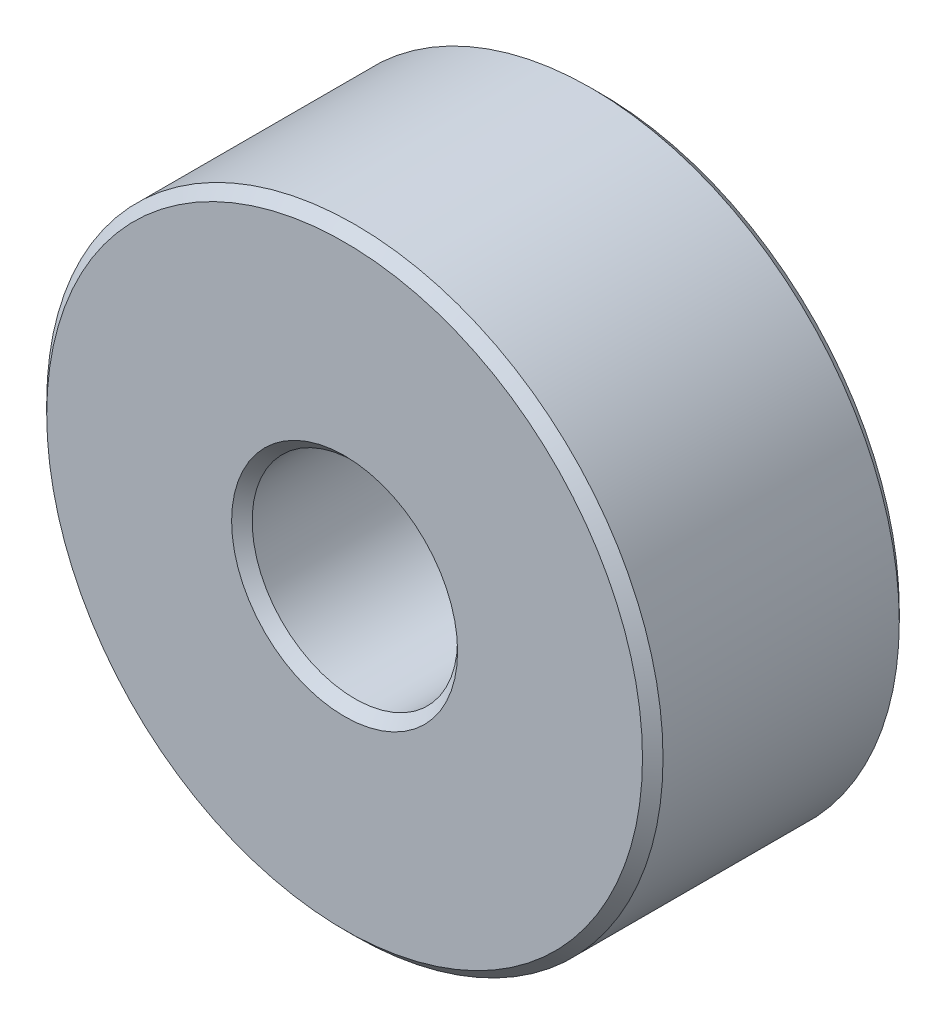
SolidWorks part; units mm, degrees
ref_plane "Front Plane" through (0, 0, 0) normal (0, 0, 1) x (1, 0, 0)
ref_plane "Top Plane" through (0, 0, 0) normal (0, 1, 0) x (1, 0, 0)
ref_plane "Right Plane" through (0, 0, 0) normal (1, 0, 0) x (0, 0, -1)
sketch "Sketch2" plane through (0, 0, 0) normal (0, 0, 1) x (1, 0, 0)
  circle A0 centre (0, 0) radius 3
  circle A1 centre (0, 0) radius 1
  dimension "D1" = 6
  dimension "D2" = 2
extrude "Boss-Extrude1" add sketch "Sketch2" along normal blind 2.5
chamfer "Chamfer1" distance 0.1 angle 45 4 edges at (1, 0, 0) (3, 0, 0) (1, 0, 2.5) (3, 0, 2.5)
